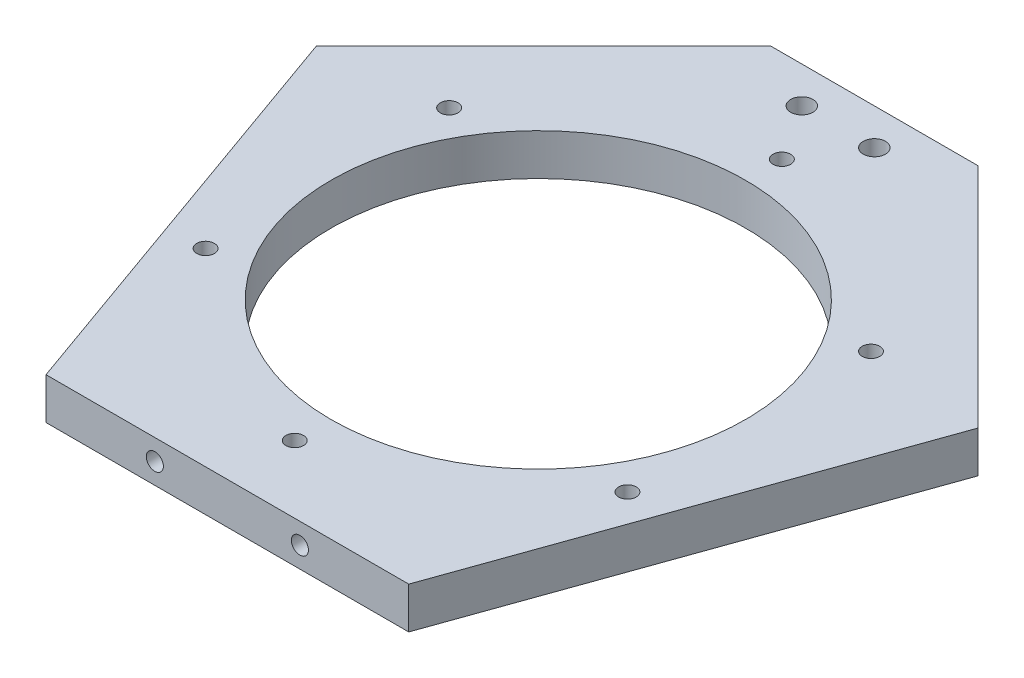
SolidWorks part; units mm, degrees
material "1060 合金"
ref_plane "前视基准面" through (0, 0, 0) normal (0, 0, 1) x (1, 0, 0)
ref_plane "上视基准面" through (0, 0, 0) normal (0, 1, 0) x (1, 0, 0)
ref_plane "右视基准面" through (0, 0, 0) normal (1, 0, 0) x (0, 0, -1)
sketch "草图2" plane through (0, 0, 0) normal (0, 1, 0) x (1, 0, 0)
  line L0 (0, 0) -> (0, 84.0702) construction
  line L7 (20, 64.8528) -> (-20, 64.8528)
  line L8 (-20, 64.8528) -> (-63.8406, 21.0122)
  line L9 (-63.8406, 21.0122) -> (-35, -60)
  line L10 (-35, -60) -> (35, -60)
  line L11 (35, -60) -> (63.8406, 21.0122)
  line L12 (63.8406, 21.0122) -> (20, 64.8528)
  circle A0 centre (0, 0) radius 40
  point P0 (0, 0)
  dimension "D3" = 80
  dimension "D1" = 62
  dimension "D2" = 60
  dimension "D4" = 70
  dimension "D5" = 60
  dimension "D6" = 40
extrude "凸台-拉伸1" add sketch "草图2" along normal mid plane 8
hole_wizard "M5 间隙孔1" positions "草图4" profile "草图3" hole size "M5" standard "GB"
sketch "草图4" plane through (0, 2.4, 0) normal (0, 1, 0) x (1, 0, 0)
  line L1 (-50, 50) -> (50, 50)
  line L2 (-50, 50) -> (-50, -50)
  line L3 (-50, -50) -> (50, -50)
  line L4 (50, 50) -> (50, -50)
  line L5 (-50, 50) -> (50, -50) construction
  line L6 (-50, -50) -> (50, 50) construction
  point P0 (-50, 50)
  point P4 (50, -50)
  point P72 (-50, -50)
  point P73 (50, 50)
  dimension "D1" = 100
sketch "草图3" plane through (-50, 2.4, -50) normal (1, 0, 0) x (0, 0, 1)
  line L0 (0, 0) -> (0, 4.8)
  line L1 (0, 4.8) -> (2.9, 4.8)
  line L2 (2.9, 4.8) -> (2.9, 0)
  line L5 (2.9, 0) -> (0, 0)
  line L11 (0, -6.35) -> (0, 107.95) construction
  dimension "通孔孔直径" = 5.8
  dimension "通孔孔深度" = 4
hole_wizard "M3 间隙孔1" positions "草图6" profile "草图5" hole size "M3" standard "GB" end condition through all
sketch "草图6" plane through (0, 4, 0) normal (0, 1, 0) x (1, 0, 0)
  line L0 (0, 0) -> (0, 47) construction
  point P0 (0, 47)
  point P9 (40.7032, 23.5)
  point P10 (40.7032, -23.5)
  point P11 (0, -47)
  point P12 (-40.7032, -23.5)
  point P13 (-40.7032, 23.5)
  dimension "D1" = 47
  dimension "D3" = 47
  dimension "D2" = 6
sketch "草图5" plane through (0, 4, -47) normal (1, 0, 0) x (0, 0, 1)
  line L0 (0, 0) -> (0, 8)
  line L1 (0, 8) -> (1.7, 8)
  line L2 (1.7, 8) -> (1.7, 0)
  line L5 (1.7, 0) -> (0, 0)
  line L11 (0, -6.35) -> (0, 107.95) construction
  dimension "通孔孔直径" = 3.4
  dimension "通孔孔深度" = 8
hole_wizard "M4 螺纹孔1" positions "草图8" profile "草图7" tap size "M4" standard "GB"
sketch "草图8" plane through (42.4264, 0, -42.4264) normal (0.7071, 0, -0.7071) x (-0.7071, 0, -0.7071)
  line L0 (0, 0) -> (0, 20.3728) construction
  line L3 (-30.2843, -4) -> (31.7157, -4) construction
  point P0 (14, 0)
  point P2 (-14, 0)
  dimension "D1" = 4
  dimension "D2" = 28
sketch "草图7" plane through (32.5269, 0, -52.3259) normal (0, 1, 0) x (-0.7071, 0, -0.7071)
  line L0 (0, 0) -> (0, 12.9914)
  line L1 (0, 12.9914) -> (1.65, 12)
  line L2 (1.65, 12) -> (1.65, 0)
  line L5 (1.65, 0) -> (0, 0)
  line L10 (0, 12.9914) -> (-1.65, 12) construction
  line L11 (0, -6.35) -> (0, 107.95) construction
  dimension "螺纹孔钻头直径" = 3.3
  dimension "螺纹孔钻头深度" = 12
  dimension "导头角度" = 118
cosmetic thread "孔螺蚊线1" parameters "D1"=12, "D2"=4
cosmetic thread "孔螺蚊线2" parameters "D1"=12, "D2"=4
mirror "镜向1" about plane through (0, 0, 0) normal (1, 0, 0) of "M4 螺纹孔1"
hole_wizard "M4 螺纹孔3" positions "草图16" profile "草图15" tap size "M4" standard "GB"
sketch "草图16" plane through (0, 0, 60) normal (0, 0, 1) x (1, 0, 0)
  line L0 (0, 0) -> (0, 17.9752) construction
  point P0 (14, 0)
  point P2 (-14, 0)
  dimension "D1" = 28
sketch "草图15" plane through (14, 0, 60) normal (1, 0, 0) x (0, -1, 0)
  line L0 (0, 0) -> (0, 15.9914)
  line L1 (0, 15.9914) -> (1.65, 15)
  line L2 (1.65, 15) -> (1.65, 0)
  line L5 (1.65, 0) -> (0, 0)
  line L10 (0, 15.9914) -> (-1.65, 15) construction
  line L11 (0, -6.35) -> (0, 107.95) construction
  dimension "螺纹孔钻头直径" = 3.3
  dimension "螺纹孔钻头深度" = 15
  dimension "导头角度" = 118
cosmetic thread "孔螺蚊线5" parameters "D1"=11, "D2"=4
cosmetic thread "孔螺蚊线6" parameters "D1"=11, "D2"=4
hole_wizard "M4 间隙孔1" positions "草图18" profile "草图17" hole size "M4" standard "GB" end condition through all
sketch "草图18" plane through (0, 4, 0) normal (0, 1, 0) x (1, 0, 0)
  line L0 (20, 64.8528) -> (-20, 64.8528) construction
  line L1 (0, 64.8528) -> (0, 38.5211) construction
  point P0 (-7, 57.8528)
  point P5 (7, 57.8528)
  dimension "D1" = 7
  dimension "D2" = 14
sketch "草图17" plane through (-7, 4, -57.8528) normal (1, 0, 0) x (0, 0, 1)
  line L0 (0, 0) -> (0, 8)
  line L1 (0, 8) -> (2.15, 8)
  line L2 (2.15, 8) -> (2.15, 0)
  line L5 (2.15, 0) -> (0, 0)
  line L11 (0, -6.35) -> (0, 107.95) construction
  dimension "通孔孔直径" = 4.3
  dimension "通孔孔深度" = 8
